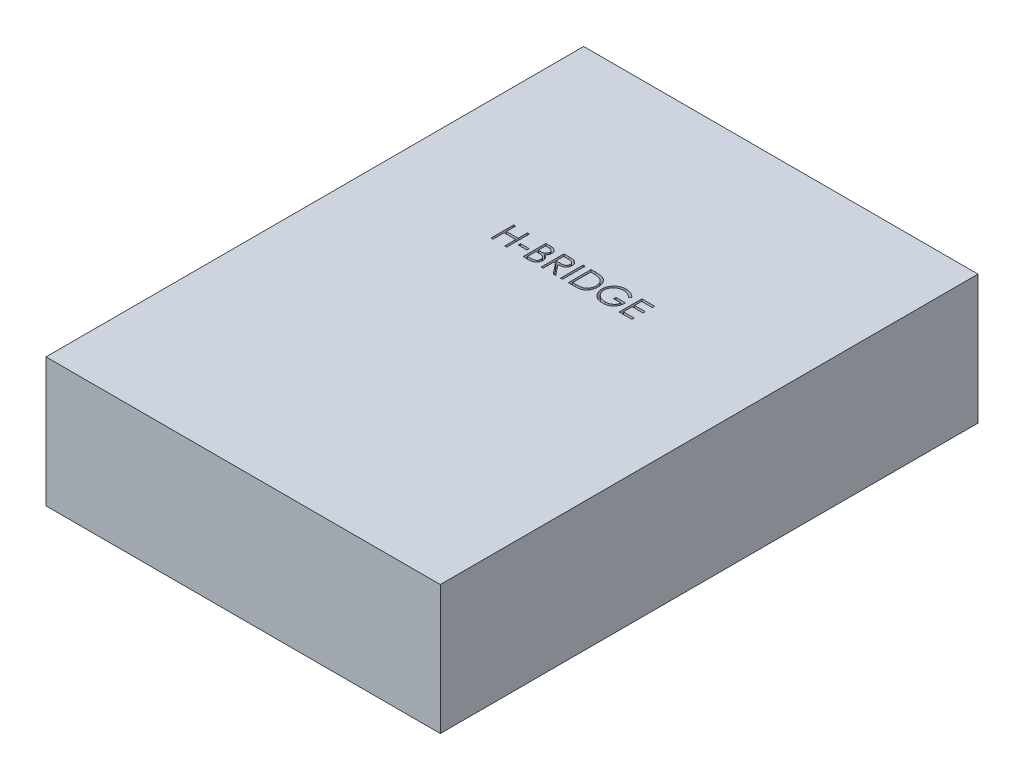
SolidWorks part; units mm, degrees
ref_plane "Front Plane" through (0, 0, 0) normal (0, 0, 1) x (1, 0, 0)
ref_plane "Top Plane" through (0, 0, 0) normal (0, 1, 0) x (1, 0, 0)
ref_plane "Right Plane" through (0, 0, 0) normal (1, 0, 0) x (0, 0, -1)
sketch "Sketch1" plane through (0, 0, 0) normal (0, 1, 0) x (1, 0, 0)
  line L1 (-27.5, -37.5) -> (27.5, -37.5)
  line L2 (-27.5, -37.5) -> (-27.5, 37.5)
  line L3 (-27.5, 37.5) -> (27.5, 37.5)
  line L4 (27.5, -37.5) -> (27.5, 37.5)
  line L5 (-27.5, -37.5) -> (27.5, 37.5) construction
  line L6 (-27.5, 37.5) -> (27.5, -37.5) construction
  point P0 (0, 0)
  dimension "D1" = 55
  dimension "D2" = 75
extrude "Boss-Extrude1" add sketch "Sketch1" along normal blind 18
sketch "Sketch2" plane through (0, 18, 0) normal (0, 1, 0) x (1, 0, 0)
  text T0 "H-BRIDGE "
extrude "Cut-Extrude1" cut sketch "Sketch2" against normal blind 1
